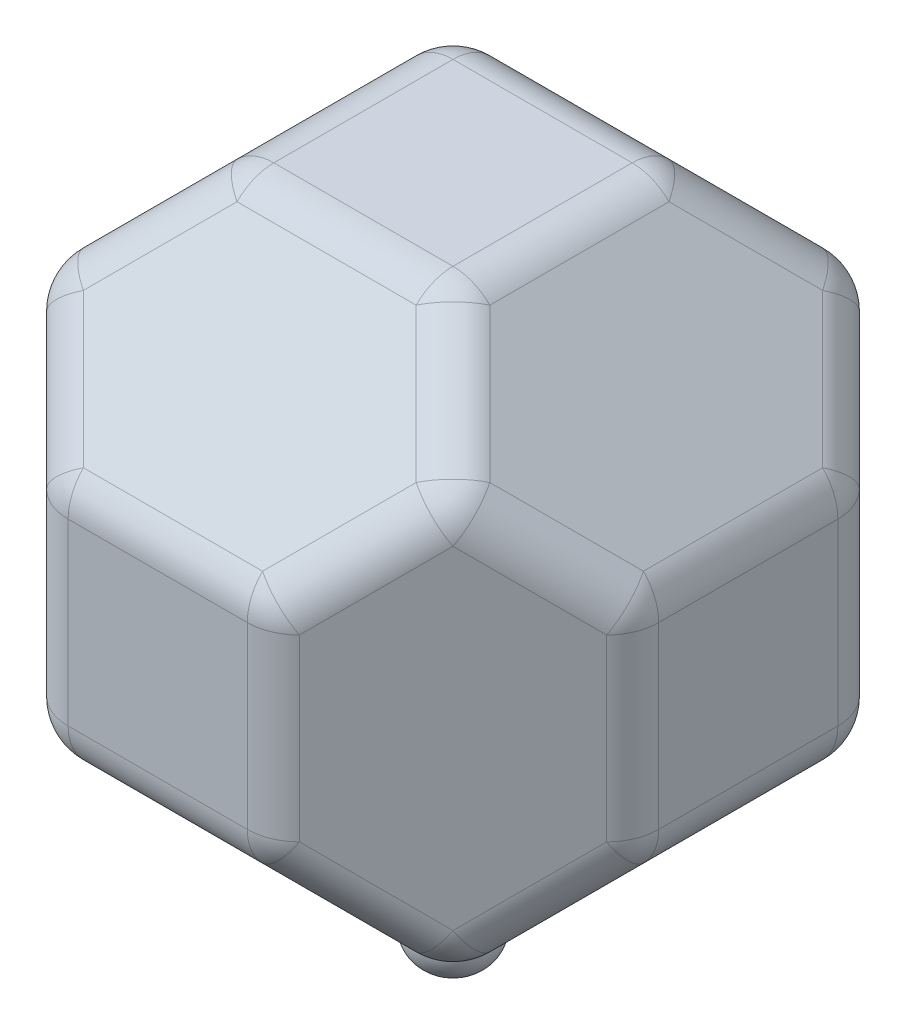
SolidWorks part; units mm, degrees
material "PE faible/moyenne densité"
ref_plane "Plan de face" through (0, 0, 0) normal (0, 0, 1) x (1, 0, 0)
ref_plane "Plan de dessus" through (0, 0, 0) normal (0, 1, 0) x (1, 0, 0)
ref_plane "Plan de droite" through (0, 0, 0) normal (1, 0, 0) x (0, 0, -1)
sketch "Esquisse1" plane through (0, 0, 0) normal (0, 0, 1) x (1, 0, 0)
  line L0 (-77.1788, 0) -> (116.5352, 0) construction
  line L1 (0, 102.4449) -> (0, -120.0068) construction
  line L2 (-32, 85) -> (32, 85)
  line L3 (32, 85) -> (85, 32)
  line L4 (85, 32) -> (85, -32)
  line L5 (-85, 32) -> (-85, -32)
  line L6 (-32, 85) -> (-85, 32)
  line L7 (-32, -85) -> (-85, -32)
  line L8 (-32, -85) -> (32, -85)
  line L9 (32, -85) -> (85, -32)
  point P12 (0, 85)
  point P13 (-85, 0)
  point P16 (85, 0)
  dimension "D1" = 32
  dimension "D2" = 32
  dimension "D3" = 85
  dimension "D4" = 85
extrude "Boss.-Extru.1" add sketch "Esquisse1" along normal blind 170
sketch "Esquisse4" plane through (0, 0, 170) normal (0, 0, 1) x (1, 0, 0)
  line L0 (-32, 32) -> (32, 32)
  line L1 (32, 32) -> (32, -32)
  line L2 (32, -32) -> (-32, -32)
  line L3 (-32, -32) -> (-32, 32)
  line L4 (-85, 32) -> (85, 32) construction
  line L5 (-32, 85) -> (-32, -85) construction
  dimension "D1" = 64
  dimension "D2" = 64
sketch "Esquisse5" plane through (0, 85, 0) normal (0, 1, 0) x (1, 0, 0)
  line L0 (-32, -85) -> (32, -85) construction
  line L1 (-32, -170) -> (-32, 0) construction
  line L2 (32, -170) -> (32, 0) construction
  line L3 (-32, -53) -> (32, -53)
  line L4 (-32, -117) -> (32, -117)
  dimension "D1" = 32
  dimension "D2" = 32
sketch3d "Esquisse3D3"
  line L0 (-32, 85, 117) -> (-32, 32, 170)
  line L1 (-32, 32, 170) -> (32, 32, 170)
  line L2 (32, 32, 170) -> (32, 85, 117)
  line L3 (32, 85, 117) -> (-32, 85, 117)
extrude "Enlèv. mat.-Extru.1" cut sketch "Esquisse3D3" along direction (0, 0, 1) on the side of the normal blind 220
sketch "Esquisse7" plane through (0, -85, 0) normal (0, -1, 0) x (-1, 0, 0)
  line L0 (32, -117) -> (-32, -117)
  line L1 (32, -53) -> (-32, -53)
sketch "Esquisse8" plane through (0, 0, 0) normal (0, 0, -1) x (-1, 0, 0)
  line L0 (-32, 32) -> (32, 32)
  line L1 (-32, -32) -> (-32, 32)
  line L2 (-32, -32) -> (32, -32)
  line L3 (32, -32) -> (32, 32)
sketch3d "Esquisse3D4"
  line L0 (32, 85, 53) -> (32, 32, 0)
  line L1 (-32, 85, 53) -> (-32, 32, 0)
  line L2 (32, 85, 53) -> (-32, 85, 53)
  line L3 (32, 32, 0) -> (-32, 32, 0)
extrude "Enlèv. mat.-Extru.2" cut sketch "Esquisse3D4" along direction (0, 0, 1) on the side against the normal blind 220
sketch3d "Esquisse3D5"
  line L0 (-32, -85, 53) -> (-32, -32, 0)
  line L1 (-32, -32, 0) -> (32, -32, 0)
  line L2 (32, -32, 0) -> (32, -85, 53)
  line L3 (32, -85, 53) -> (-32, -85, 53)
extrude "Enlèv. mat.-Extru.3" cut sketch "Esquisse3D5" along direction (0, 0, 1) on the side against the normal blind 220
sketch3d "Esquisse3D6"
  line L0 (32, -85, 117) -> (32, -32, 170)
  line L1 (32, -32, 170) -> (-32, -32, 170) construction
  line L2 (32, 32, 170) -> (32, -32, 170) construction
  line L3 (32, -32, 170) -> (-32, -32, 170)
  line L4 (-32, -32, 170) -> (-32, -85, 117)
  line L5 (-32, -85, 117) -> (32, -85, 117)
extrude "Enlèv. mat.-Extru.4" cut sketch "Esquisse3D6" along direction (0, 0, 1) on the side against the normal blind 220
sketch "Esquisse12" plane through (85, 0, 0) normal (1, 0, 0) x (0, 0, -1)
  line L0 (-85, 32) -> (-85, -32) construction
  line L1 (-170, 32) -> (0, 32) construction
  line L2 (-170, -32) -> (0, -32) construction
  line L3 (-117, 32) -> (-117, -32)
  line L4 (-53, 32) -> (-53, -32)
  dimension "D1" = 32
  dimension "D2" = 32
sketch "Esquisse13" plane through (-85, 0, 0) normal (-1, 0, 0) x (0, 0, 1)
  line L0 (117, 32) -> (117, -32)
  line L1 (53, 32) -> (53, -32)
sketch3d "Esquisse3D13"
  line L0 (32, 32, 170) -> (85, 32, 117)
  line L1 (85, 32, 117) -> (85, -32, 117)
  line L2 (85, -32, 117) -> (32, -32, 170)
  line L3 (32, -32, 170) -> (32, 32, 170)
extrude "Enlèv. mat.-Extru.11" cut sketch "Esquisse3D13" along direction (-1, 0, 0) on the side against the normal blind 220
sketch "Esquisse16" plane through (0, -32, 0) normal (0, 1, 0) x (1, 0, 0)
  line L0 (32, -170) -> (85, -117)
  line L1 (85, -117) -> (85, -170)
  line L2 (85, -170) -> (32, -170)
  line L3 (32, -170) -> (24.6697, -219.3148)
  line M1 (85, -170) -> (85, -117)
  line M2 (85, -117) -> (32, -170)
  line M3 (32, -170) -> (85, -170)
extrude "Enlèv. mat.-Extru.13" cut sketch "Esquisse16" against normal blind 220 and the other way blind 220 contours M3 M1 M2
sketch3d "Esquisse3D15"
  line L0 (-85, -32, 117) -> (-32, -32, 170)
  line L1 (-32, -32, 170) -> (-32, 32, 170)
  line L2 (-32, 32, 170) -> (-85, 32, 117)
  line L3 (-85, 32, 117) -> (-85, -32, 117)
extrude "Enlèv. mat.-Extru.14" cut sketch "Esquisse3D15" along direction (0, 0, 1) on the side against the normal blind 220
sketch "Esquisse17" plane through (0, -32, 0) normal (0, 1, 0) x (1, 0, 0)
  line L0 (-85, -117) -> (-32, -170)
  line L1 (-32, -170) -> (-85, -170)
  line L2 (-85, -170) -> (-85, -117)
extrude "Enlèv. mat.-Extru.15" cut sketch "Esquisse17" against normal blind 220 and the other way blind 220
sketch3d "Esquisse3D16"
  line L0 (-32, 32, 0) -> (-85, 32, 53)
  line L1 (-85, 32, 53) -> (-85, -32, 53)
  line L2 (-85, -32, 53) -> (-32, -32, 0)
  line L3 (-32, -32, 0) -> (-32, 32, 0)
extrude "Enlèv. mat.-Extru.16" cut sketch "Esquisse3D16" along direction (0, 0, 1) on the side against the normal blind 220
sketch "Esquisse18" plane through (0, -32, 0) normal (0, 1, 0) x (1, 0, 0)
  line L0 (-32, 0) -> (-85, -53)
  line L1 (-85, -53) -> (-85, 0)
  line L2 (-85, 0) -> (-32, 0)
extrude "Enlèv. mat.-Extru.17" cut sketch "Esquisse18" against normal blind 220 and the other way blind 220
sketch3d "Esquisse3D17"
  line L0 (85, 32, 53) -> (32, 32, 0)
  line L1 (32, 32, 0) -> (32, -32, 0)
  line L2 (32, -32, 0) -> (85, -32, 53)
  line L3 (85, -32, 53) -> (85, 32, 53)
extrude "Enlèv. mat.-Extru.18" cut sketch "Esquisse3D17" along direction (0, 0, 1) on the side of the normal blind 220
sketch "Esquisse19" plane through (0, -32, 0) normal (0, 1, 0) x (1, 0, 0)
  line L0 (85, -53) -> (32, 0)
  line L1 (32, 0) -> (85, 0)
  line L2 (85, 0) -> (85, -53)
extrude "Enlèv. mat.-Extru.19" cut sketch "Esquisse19" against normal blind 220 and the other way blind 220
sketch "Esquisse21" plane through (32, 0, 0) normal (-1, 0, 0) x (0, 0, 1)
  line L0 (117, 85) -> (170, 32)
  line L1 (170, 32) -> (170, 85)
  line L2 (170, 85) -> (117, 85)
extrude "Enlèv. mat.-Extru.20" cut sketch "Esquisse21" against normal blind 220 and the other way blind 220
sketch "Esquisse23" plane through (32, 0, 0) normal (-1, 0, 0) x (0, 0, 1)
  line L0 (0, 32) -> (53, 85)
  line L1 (53, 85) -> (0, 85)
  line L2 (0, 85) -> (0, 32)
extrude "Enlèv. mat.-Extru.21" cut sketch "Esquisse23" against normal blind 220 and the other way blind 220
sketch "Esquisse24" plane through (32, 0, 0) normal (-1, 0, 0) x (0, 0, 1)
  line L0 (0, -32) -> (53, -85)
  line L1 (53, -85) -> (0, -85)
  line L2 (0, -85) -> (0, -32)
extrude "Enlèv. mat.-Extru.22" cut sketch "Esquisse24" against normal blind 220 and the other way blind 220
sketch "Esquisse25" plane through (-32, 0, 0) normal (1, 0, 0) x (0, 0, -1)
  line L0 (-170, -32) -> (-170, -85)
  line L1 (-170, -85) -> (-117, -85)
  line L2 (-117, -85) -> (-170, -32)
extrude "Enlèv. mat.-Extru.23" cut sketch "Esquisse25" against normal blind 220 and the other way blind 220
fillet "Congé2" radius 15 48 edges
sketch "Esquisse26" plane through (0, -85, 0) normal (0, -1, 0) x (1, 0, 0)
  circle A0 centre (0, 85) radius 11.4219
extrude "Boss.-Extru.2" add sketch "Esquisse26" along normal blind 30
fillet "Congé6" radius 10 1 edges at (11.4219, -115, 85)
